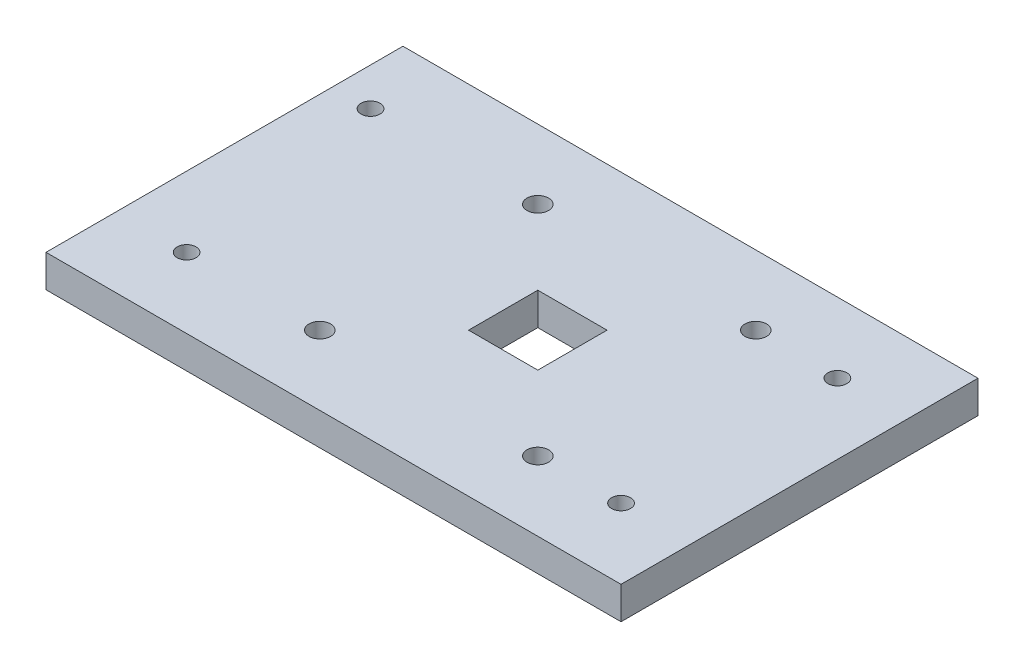
SolidWorks part; units mm, degrees
ref_plane "Front Plane" through (0, 0, 0) normal (0, 0, 1) x (1, 0, 0)
ref_plane "Top Plane" through (0, 0, 0) normal (0, 1, 0) x (1, 0, 0)
ref_plane "Right Plane" through (0, 0, 0) normal (1, 0, 0) x (0, 0, -1)
sketch "Sketch1" plane through (0, 0, 0) normal (0, 1, 0) x (1, 0, 0)
  line L0 (-57.93, -33) -> (48.39, -33)
  line L1 (-57.93, -33) -> (-57.93, 33)
  line L2 (48.39, -33) -> (48.39, 33)
  line L3 (-57.93, 33) -> (48.39, 33)
  line L6 (-6.4, 6.4) -> (6.4, 6.4)
  line L7 (-6.4, 6.4) -> (-6.4, -6.4)
  line L8 (6.4, 6.4) -> (6.4, -6.4)
  line L9 (-6.4, -6.4) -> (6.4, -6.4)
  circle A0 centre (20.1525, -20.1525) radius 2 construction
  circle A1 centre (20.1525, 20.1525) radius 2 construction
  circle A2 centre (-20.1525, -20.1525) radius 2 construction
  circle A3 centre (-20.1525, 20.1525) radius 2 construction
  circle A4 centre (20.1525, -20.1525) radius 2
  circle A5 centre (20.1525, 20.1525) radius 2
  circle A6 centre (-20.1525, -20.1525) radius 2
  circle A7 centre (-20.1525, 20.1525) radius 2
  point P1 (0, 0)
  dimension "D1" = 66
  dimension "D2" = 106.32
  dimension "D3" = 12.8
  dimension "D4" = 6.4
  dimension "D5" = 48.39
  dimension "D6" = 33
  dimension "D7" = 6.4
  dimension "D8" = 12.8
extrude "Boss-Extrude1" add sketch "Sketch1" along normal blind 6
sketch "Sketch4" plane through (0, 6, 0) normal (0, 1, 0) x (1, 0, 0)
  line L0 (48.39, 33) -> (-57.93, 33) construction
  line L1 (-57.93, 33) -> (-57.93, -33) construction
  line L2 (-57.93, -33) -> (48.39, -33) construction
  line L3 (48.39, -33) -> (48.39, 33) construction
  circle A0 centre (-50.93, 20) radius 1.75
  circle A1 centre (-44.93, -20) radius 1.75
  circle A2 centre (35.39, -20) radius 1.75
  circle A3 centre (35.39, 20) radius 1.75
  dimension "D1" = 13
  dimension "D2" = 7
  dimension "D3" = 3.5
  dimension "D4" = 3.5
  dimension "D7" = 3.5
  dimension "D8" = 13
  dimension "D9" = 13
  dimension "D10" = 3.5
  dimension "D11" = 13
  dimension "D12" = 13
  dimension "D5" = 13
  dimension "D6" = 13
extrude "Cut-Extrude1" cut sketch "Sketch4" against normal through all
